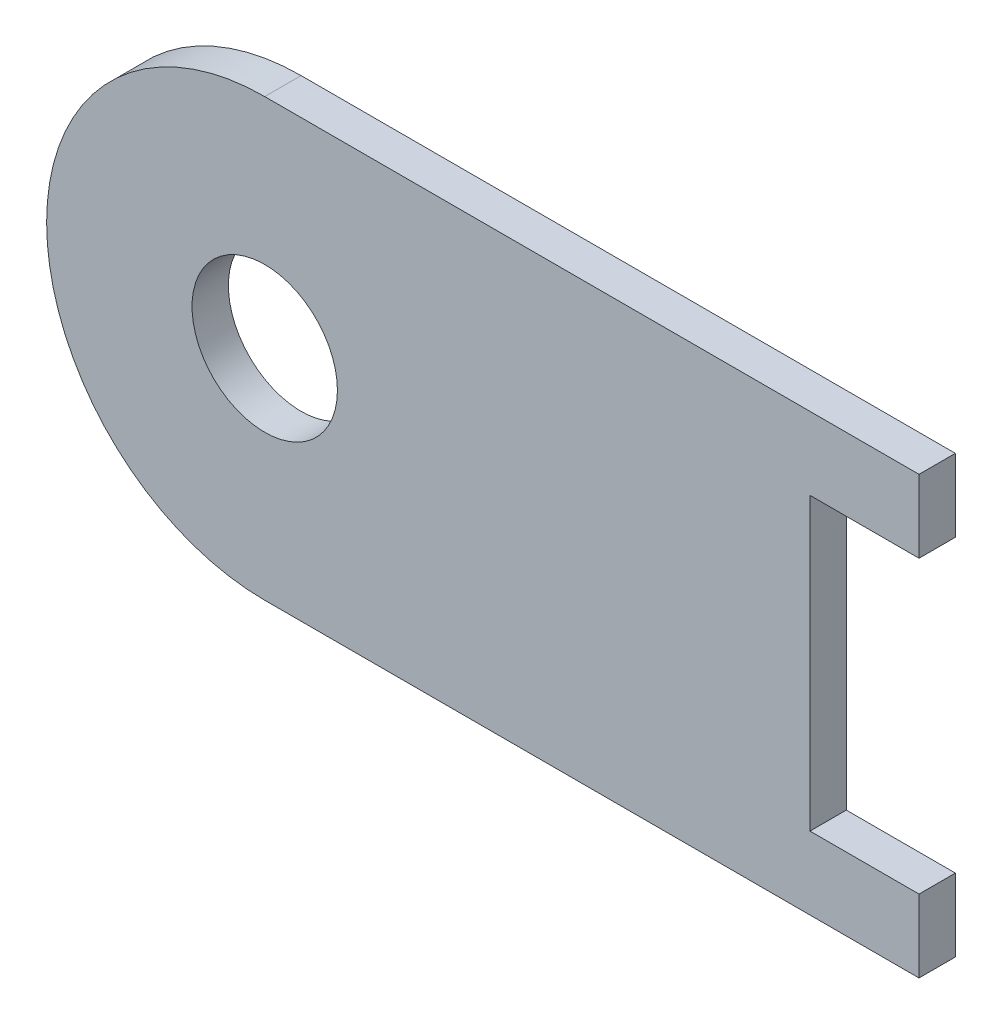
SolidWorks part; units mm, degrees
ref_plane "Front Plane" through (0, 0, 0) normal (0, 0, 1) x (1, 0, 0)
ref_plane "Top Plane" through (0, 0, 0) normal (0, 1, 0) x (1, 0, 0)
ref_plane "Right Plane" through (0, 0, 0) normal (1, 0, 0) x (0, 0, -1)
sketch "Sketch1" plane through (0, 0, 0) normal (0, 0, 1) x (1, 0, 0)
  line L0 (-28.3202, 0) -> (151.6798, 0)
  line L2 (-28.3202, 120) -> (151.6798, 120)
  line L4 (151.6798, 120) -> (151.6798, 100)
  line L5 (151.6798, 100) -> (121.6798, 100)
  line L6 (121.6798, 100) -> (121.6798, 20)
  line L7 (121.6798, 20) -> (151.6798, 20)
  line L8 (151.6798, 20) -> (151.6798, 0)
  line L9 (121.6798, 120) -> (121.6798, 0) construction
  arc A0 (-28.3202, 120) -> (-28.3202, 0) centre (-28.3202, 60) ccw
  circle A1 centre (-28.3202, 60) radius 20
  point P12 (151.6798, 110)
  dimension "D3" = 60
  dimension "D6" = 40
  dimension "D1" = 180
  dimension "D2" = 180
  dimension "D4" = 80
  dimension "D5" = 30
extrude "Boss-Extrude2" add sketch "Sketch1" along normal blind 10
sketch "Sketch3" plane through (0, 0, 0) normal (0, 0, 1) x (1, 0, 0)
  line L0 (46.6798, 120) -> (46.6798, 109.4207)
  line L1 (151.6798, 120) -> (-28.3202, 120) construction
  line L2 (151.6798, 100) -> (151.6798, 120) construction
  line L3 (46.6798, 109.4207) -> (64.7014, 95.6183)
  line L4 (64.7014, 95.6183) -> (64.7014, 39.6819)
  line L5 (64.7014, 39.6819) -> (46.6798, 21.6604)
  line L6 (46.6798, 21.6604) -> (46.6798, 0)
  line L7 (-28.3202, 0) -> (151.6798, 0) construction
  dimension "D1" = 105
  dimension "D2" = 55.9363
